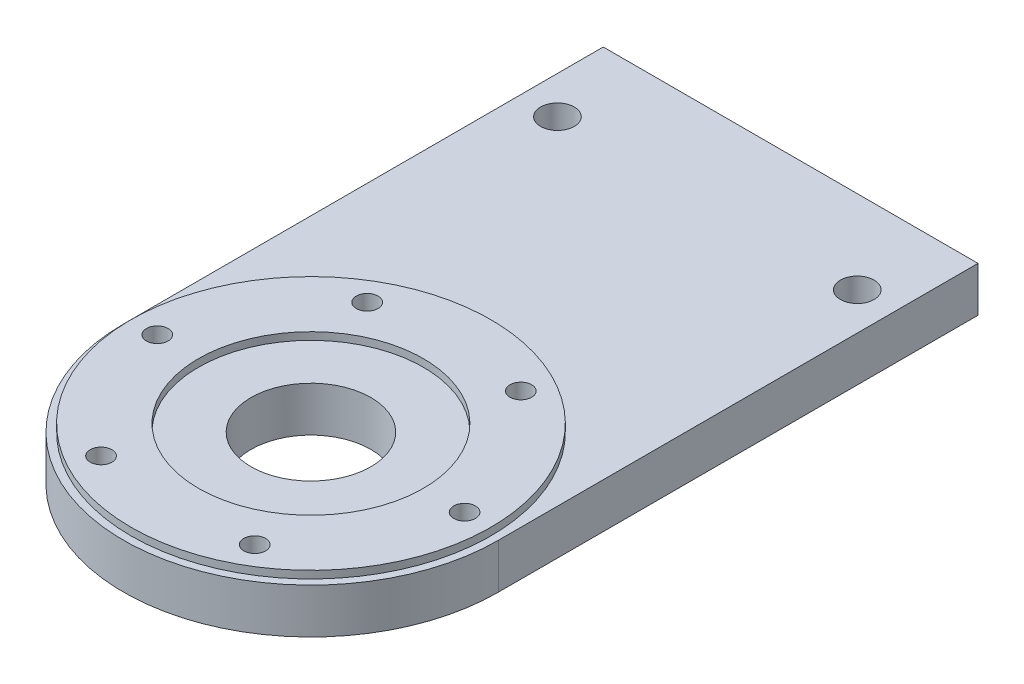
SolidWorks part; units mm, degrees
material "Aleación 6061"
ref_plane "Alzado" through (0, 0, 0) normal (0, 0, 1) x (1, 0, 0)
ref_plane "Planta" through (0, 0, 0) normal (0, 1, 0) x (1, 0, 0)
ref_plane "Vista lateral" through (0, 0, 0) normal (1, 0, 0) x (0, 0, -1)
sketch "Sk_Pared" plane through (0, 0, 0) normal (0, 1, 0) x (1, 0, 0)
  line L1 (-25, -490) -> (25, -490)
  line L2 (-25, -490) -> (-25, -426)
  line L3 (-25, -426) -> (25, -426)
  line L4 (25, -490) -> (25, -426)
  line L5 (-25, -490) -> (25, -426) construction
  line L6 (-25, -426) -> (25, -490) construction
  point P0 (0, -458)
  dimension "D1" = 50
  dimension "D2" = 64
  dimension "D3" = 458
extrude "Pared" add sketch "Sk_Pared" along normal blind 6 from offset 27.5
sketch "Sk_Cabeza" plane through (0, 0, 0) normal (0, 1, 0) x (1, 0, 0)
  circle A0 centre (0, -490) radius 25
  dimension "D1" = 50
  dimension "D2" = 490
extrude "Cabeza" add sketch "Sk_Cabeza" along normal blind 6 from offset 27.5
sketch "Sk_Asiento_1mm" plane through (0, 0, 0) normal (0, 1, 0) x (1, 0, 0)
  circle A0 centre (0, -490) radius 24
  circle A1 centre (0, -490) radius 15
  dimension "D1" = 48
  dimension "D3" = 30
  dimension "D2" = 490
  dimension "D4" = 490
extrude "Asiento_1mm" add sketch "Sk_Asiento_1mm" along normal blind 1 from offset 21.5
sketch "Sk_Paso_central" plane through (0, 0, 0) normal (0, 1, 0) x (1, 0, 0)
  circle A0 centre (0, -490) radius 8
  dimension "D1" = 16
  dimension "D2" = 490
extrude "Paso_central" cut sketch "Sk_Paso_central" along normal blind 7 from offset 27.5
sketch "Sk_Pasantes_M2-5_estator_J5" plane through (0, 0, 0) normal (0, 1, 0) x (1, 0, 0)
  circle A0 centre (20.5, -490) radius 1.45
  circle A1 centre (10.25, -507.7535) radius 1.45
  circle A2 centre (-10.25, -507.7535) radius 1.45
  circle A3 centre (-20.5, -490) radius 1.45
  circle A4 centre (-10.25, -472.2465) radius 1.45
  circle A5 centre (10.25, -472.2465) radius 1.45
  dimension "D1" = 2.9
  dimension "D4" = 2.9
  dimension "D7" = 2.9
  dimension "D10" = 2.9
  dimension "D13" = 2.9
  dimension "D16" = 2.9
  dimension "D2" = 20.5
  dimension "D3" = 490
  dimension "D5" = 10.25
  dimension "D6" = 507.7535
  dimension "D8" = 10.25
  dimension "D9" = 507.7535
  dimension "D11" = 20.5
  dimension "D12" = 490
  dimension "D14" = 10.25
  dimension "D15" = 472.2465
  dimension "D17" = 10.25
  dimension "D18" = 472.2465
extrude "Pasantes_M2-5_estator_J5" cut sketch "Sk_Pasantes_M2-5_estator_J5" along normal blind 7 from offset 27.5
sketch "Sk_Cajas_M2-5_J5" plane through (0, 0, 0) normal (0, 1, 0) x (1, 0, 0)
  circle A0 centre (10.25, -507.7535) radius 2.75
  circle A1 centre (-10.25, -507.7535) radius 2.75
  circle A2 centre (-10.25, -472.2465) radius 2.75
  circle A3 centre (10.25, -472.2465) radius 2.75
  dimension "D1" = 5.5
  dimension "D4" = 5.5
  dimension "D7" = 5.5
  dimension "D10" = 5.5
  dimension "D2" = 10.25
  dimension "D3" = 507.7535
  dimension "D5" = 10.25
  dimension "D6" = 507.7535
  dimension "D8" = 10.25
  dimension "D9" = 472.2465
  dimension "D11" = 10.25
  dimension "D12" = 472.2465
extrude "Cajas_M2-5_J5" cut sketch "Sk_Cajas_M2-5_J5" along normal blind 2.5 from offset 27.5
sketch "Sk_Pasantes_M4_angulos" plane through (0, 0, 0) normal (0, 1, 0) x (1, 0, 0)
  circle A0 centre (-20, -437.11) radius 2.25
  circle A1 centre (20, -437.11) radius 2.25
  dimension "D1" = 4.5
  dimension "D4" = 4.5
  dimension "D2" = 20
  dimension "D3" = 437.11
  dimension "D5" = 20
  dimension "D6" = 437.11
extrude "Pasantes_M4_angulos" cut sketch "Sk_Pasantes_M4_angulos" along normal blind 6 from offset 27.5
